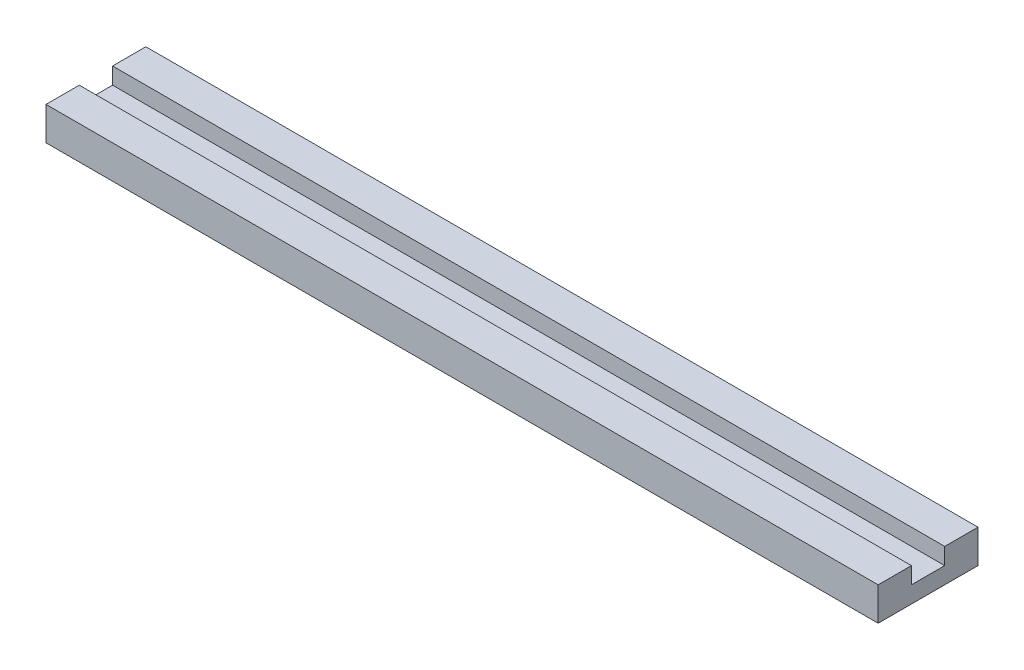
SolidWorks part; units mm, degrees
ref_plane "前视基准面" through (0, 0, 0) normal (0, 0, 1) x (1, 0, 0)
ref_plane "上视基准面" through (0, 0, 0) normal (0, 1, 0) x (1, 0, 0)
ref_plane "右视基准面" through (0, 0, 0) normal (1, 0, 0) x (0, 0, -1)
sketch "草图1" plane through (0, 0, 0) normal (1, 0, 0) x (0, 0, -1)
  line L0 (-2, 2) -> (-6, 2)
  line L5 (-2, 2) -> (-2, 0)
  line L6 (-2, 0) -> (2, 0)
  line L7 (-6, 2) -> (-6, -2)
  line L8 (-6, -2) -> (6, -2)
  line L9 (6, 2) -> (6, -2)
  line L10 (2, 2) -> (6, 2)
  line L11 (0, 0) -> (0, 2.0853) construction
  line L12 (2, 2) -> (2, 0)
  point P0 (0, 0)
  point P1 (0, -2.8405)
  point P12 (0, -2)
  dimension "D1" = 4
  dimension "D2" = 4
  dimension "D3" = 6
  dimension "D4" = 2
extrude "凸台-拉伸1" add sketch "草图1" along normal mid plane 100
